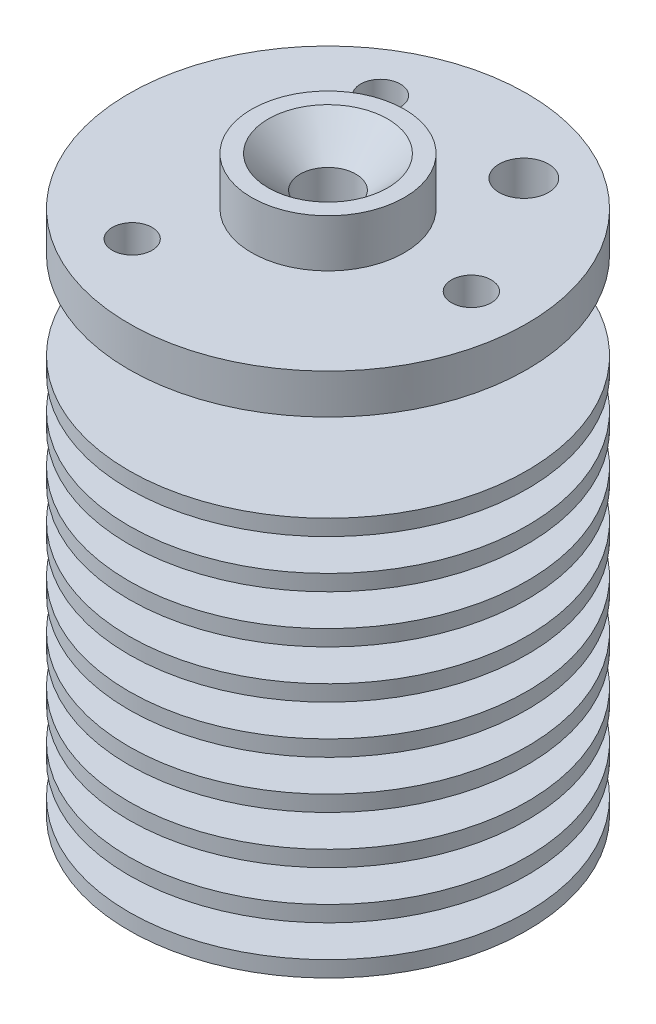
SolidWorks part; units mm, degrees
ref_plane "Front Plane" through (0, 0, 0) normal (0, 0, 1) x (1, 0, 0)
ref_plane "Top Plane" through (0, 0, 0) normal (0, 1, 0) x (1, 0, 0)
ref_plane "Right Plane" through (0, 0, 0) normal (1, 0, 0) x (0, 0, -1)
sketch "Sketch1" plane through (0, 0, 0) normal (0, 0, 1) x (1, 0, 0)
  line L0 (-2.5, 0) -> (-2.5, 6)
  line L1 (-2.5, 6) -> (-0.8, 6)
  line L2 (-0.8, 6) -> (-0.8, 33)
  line L3 (-0.8, 33) -> (-12.5, 33)
  line L4 (-12.5, 33) -> (-12.5, 0)
  line L5 (-12.5, 0) -> (-2.5, 0)
  line L6 (0, 0) -> (0, 131.8203) construction
  line L7 (0, 0) -> (-2.5, 0) construction
  dimension "D1" = 5
  dimension "D2" = 12.5
  dimension "D3" = 6
  dimension "D4" = 33
  dimension "D5" = 1.6
revolve "Revolve1" add sketch "Sketch1" angle 360 about L6
cosmetic thread "Rosca cosmética1" parameters "D1"=4, "D2"=6
ref_axis "Axis1" through (0, 33, 0) along (0, -1, 0)
sketch "Sketch2" plane through (0, 0, 0) normal (1, 0, 0) x (0, 0, -1)
  line L0 (12.5, 30) -> (3.5, 30)
  line L1 (12.5, 0) -> (12.5, 33) construction
  line L2 (3.5, 30) -> (3.5, 28)
  line L3 (3.5, 28) -> (12.5, 28)
  line L4 (12.5, 0) -> (12.5, 33) construction
  line L5 (12.5, 28) -> (12.5, 30)
  line L6 (12.5, 33) -> (-12.5, 33) construction
  dimension "D1" = 9
  dimension "D2" = 3
  dimension "D3" = 2
revolve "Cut-Revolve1" cut sketch "Sketch2" angle 360 about axis through (0, 33, 0) along (0, -1, 0)
pattern_linear "LPattern1" count 11 spacing 3 along (0, -1, 0) of "Cut-Revolve1"
sketch "Croquis2" plane through (0, 28, 0) normal (0, 1, 0) x (1, 0, 0)
  circle A0 centre (0, 0) radius 3.5 construction
  circle A1 centre (0, 0) radius 12.5 construction
  circle A2 centre (0, 0) radius 3.5
  circle A3 centre (0, 0) radius 12.5
extrude "Cortar-Extruir2" cut sketch "Croquis2" against normal up to next
sketch "Sketch3" plane through (0, 33, 0) normal (0, 1, 0) x (1, 0, 0)
  circle A0 centre (0, 0) radius 4.8
  dimension "D1" = 9.6
extrude "Boss-Extrude1" add sketch "Sketch3" along normal blind 3
sketch "Sketch4" plane through (0, 36, 0) normal (0, 1, 0) x (1, 0, 0)
  circle A0 centre (0, 0) radius 1.75
  dimension "D1" = 3.5
extrude "Cut-Extrude1" cut sketch "Sketch4" against normal through all
chamfer "Chamfer1" distance 2 angle 45 1 edges at (0, 36, 1.75)
sketch "Sketch7" plane through (0, 30, 0) normal (0, 1, 0) x (1, 0, 0)
  circle A1 centre (0, 0) radius 3.5 construction
  circle A2 centre (0, 0) radius 12.5
  circle A3 centre (0, 0) radius 3.5
  circle A4 centre (0, 0) radius 12.5 construction
extrude "Cut-Extrude5" cut sketch "Sketch7" along normal blind 0.5
sketch "Sketch5" plane through (0, 33, 0) normal (0, 1, 0) x (1, 0, 0)
  circle A0 centre (0, 0) radius 9 construction
  circle A1 centre (9, 0) radius 1.25
  circle A2 centre (-4.5, -7.7942) radius 1.25
  circle A3 centre (-4.5, 7.7942) radius 1.25
  point P11 (0, 0)
  dimension "D1" = 18
  dimension "D2" = 2.5
  dimension "D3" = 3
extrude "Cut-Extrude2" cut sketch "Sketch5" against normal up to next
cosmetic thread "Rosca cosmética2" parameters "D2"=3
cosmetic thread "Rosca cosmética3" parameters "D2"=3
cosmetic thread "Rosca cosmética4" parameters "D2"=3
sketch "Sketch8" plane through (0, 1, 0) normal (0, 1, 0) x (1, 0, 0)
  circle A1 centre (0, 0) radius 3.5
  circle A2 centre (0, 0) radius 5
  circle A3 centre (0, 0) radius 3.5 construction
  dimension "D1" = 1.5
extrude "Boss-Extrude2" add sketch "Sketch8" along normal up to surface (8 mm away) up to face at (0, 9, 3.5)
sketch "Croquis1" plane through (0, 33, 0) normal (0, 1, 0) x (1, 0, 0)
  line L0 (0, 0) -> (16.7557, 0) construction
  line L1 (0, 0) -> (4.5, 7.7942) construction
  circle A0 centre (4.5, 7.7942) radius 1.55
  dimension "D2" = 3.1
  dimension "D1" = 60
  dimension "D3" = 9
extrude "Cortar-Extruir1" cut sketch "Croquis1" against normal up to next
